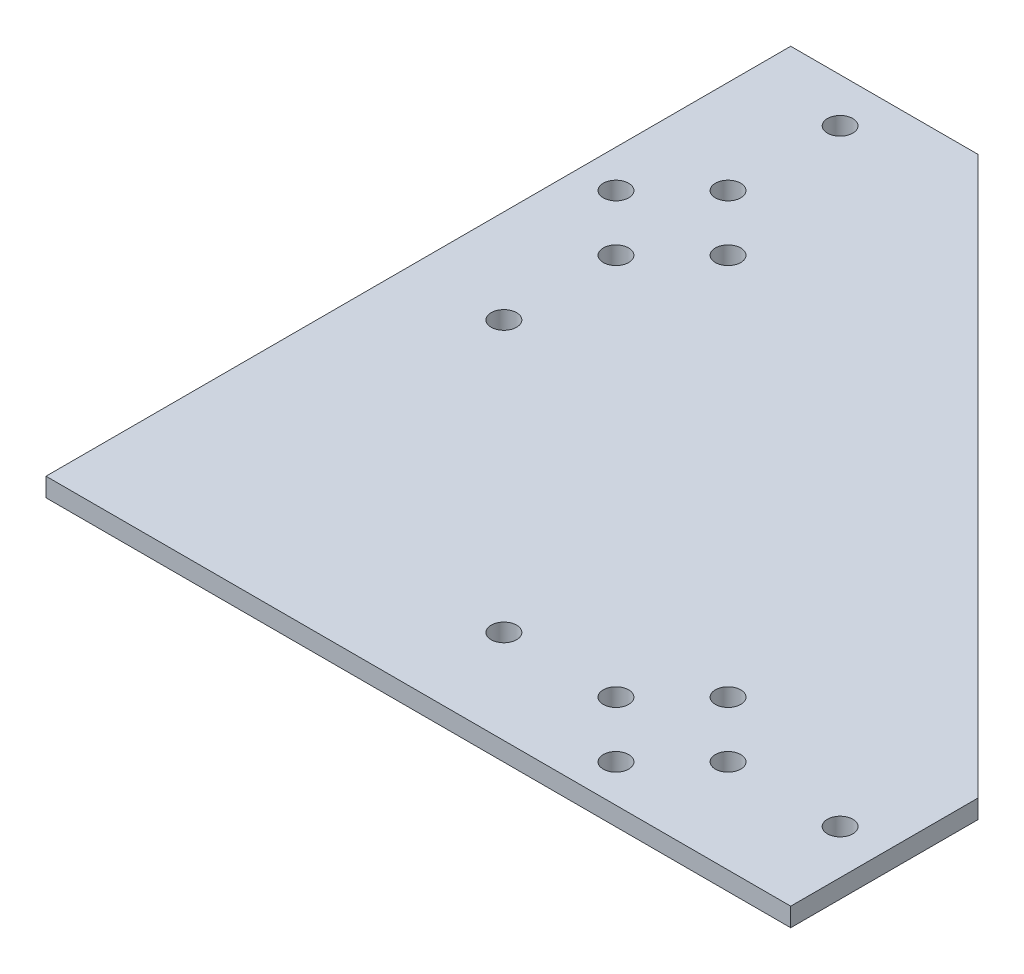
SolidWorks part; units mm, degrees
ref_plane "Front Plane" through (0, 0, 0) normal (0, 0, 1) x (1, 0, 0)
ref_plane "Top Plane" through (0, 0, 0) normal (0, 1, 0) x (1, 0, 0)
ref_plane "Right Plane" through (0, 0, 0) normal (1, 0, 0) x (0, 0, -1)
sketch "Sketch1" plane through (0, 0, 0) normal (0, 1, 0) x (1, 0, 0)
  line L0 (0, 0) -> (0, 126.25)
  line L1 (0, 126.25) -> (31.75, 126.25)
  line L2 (31.75, 126.25) -> (126.25, 31.75)
  line L3 (126.25, 31.75) -> (126.25, 0)
  line L4 (126.25, 0) -> (0, 0)
  line L5 (6.375, 90.25) -> (25.375, 90.25) construction
  line L6 (0, 0) -> (31.75, 0)
  line L7 (0, 0) -> (0, 31.75)
  line L8 (0, 31.75) -> (31.75, 31.75) construction
  line L9 (31.75, 0) -> (31.75, 31.75) construction
  line L10 (0, 0) -> (31.75, 31.75) construction
  line L11 (0, 31.75) -> (31.75, 0) construction
  line L12 (15.875, 99.75) -> (15.875, 80.75) construction
  line L13 (15.875, 80.75) -> (15.875, 61.75) construction
  line L14 (15.875, 99.75) -> (15.875, 118.75) construction
  circle A0 centre (15.875, 61.75) radius 2.5 construction
  circle A1 centre (15.875, 80.75) radius 2.5 construction
  circle A2 centre (15.875, 99.75) radius 2.5 construction
  circle A3 centre (15.875, 118.75) radius 2.5 construction
  circle A4 centre (61.75, 15.875) radius 2.5 construction
  circle A5 centre (80.75, 15.875) radius 2.5 construction
  circle A6 centre (99.75, 15.875) radius 2.5 construction
  circle A7 centre (118.75, 15.875) radius 2.5 construction
  circle A8 centre (6.375, 90.25) radius 2.5 construction
  circle A9 centre (25.375, 90.25) radius 2.5 construction
  circle A10 centre (90.25, 6.375) radius 2.5 construction
  circle A11 centre (90.25, 25.375) radius 2.5 construction
  point P9 (15.875, 15.875)
  point P30 (15.875, 90.25)
  point P31 (15.875, 90.25)
  point P32 (0, 0)
  point P37 (15.875, 31.75)
  dimension "D2" = 5
  dimension "D1" = 31.75
  dimension "D3" = 19
  dimension "D4" = 7.5
  dimension "D5" = 30
extrude "Boss-Extrude1" add sketch "Sketch1" along normal blind 3.175 contours L4 L3 L2 L1 L0
hole_wizard "#8 Clearance Hole1" positions "Sketch2" profile "Sketch3" hole size "#8" standard "ANSI Inch" end condition through all
sketch "Sketch2" plane through (0, 3.175, 0) normal (0, 1, 0) x (1, 0, 0)
  point P0 (15.875, 61.75)
  point P2 (15.875, 80.75)
  point P4 (6.375, 90.25)
  point P6 (25.375, 90.25)
  point P8 (15.875, 99.75)
  point P10 (15.875, 118.75)
  point P12 (118.75, 15.875)
  point P14 (99.75, 15.875)
  point P16 (90.25, 25.375)
  point P18 (90.25, 6.375)
  point P20 (80.75, 15.875)
  point P22 (61.75, 15.875)
  point P25 (20.2716, 56.7416)
  point P27 (0, 0)
  point P29 (0, 0)
  point P31 (0, 0)
  point P33 (0, 0)
  point P35 (0, 0)
  point P37 (0, 0)
  point P39 (0, 0)
  point P41 (0, 0)
  point P43 (0, 0)
  point P45 (0, 0)
  point P47 (0, 0)
sketch "Sketch3" plane through (15.875, 3.175, -61.75) normal (1, 0, 0) x (0, 0, 1)
  line L0 (0, 0) -> (0, 3.175)
  line L1 (0, 3.175) -> (2.1526, 3.175)
  line L2 (2.1526, 3.175) -> (2.1526, 0)
  line L5 (2.1526, 0) -> (0, 0)
  line L11 (0, -6.35) -> (0, 107.95) construction
  dimension "Thru Hole Dia." = 4.3053
  dimension "Thru Hole Depth" = 3.175
